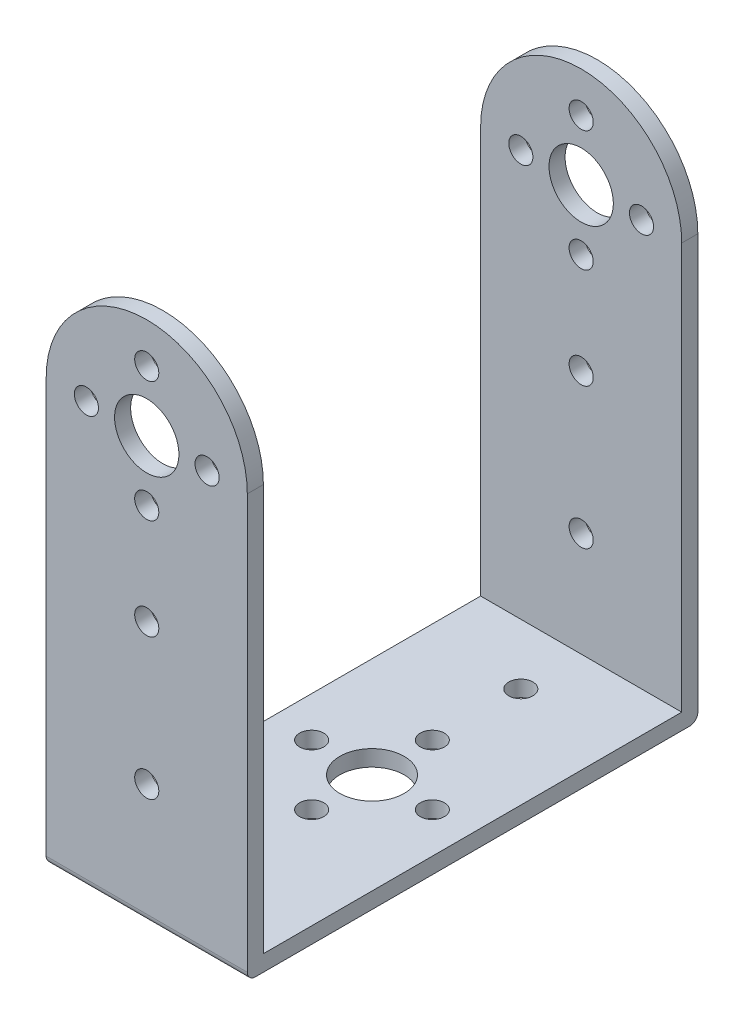
SolidWorks part; units mm, degrees
material "1060 Alloy"
ref_plane "Front Plane" through (0, 0, 0) normal (0, 0, 1) x (1, 0, 0)
ref_plane "Top Plane" through (0, 0, 0) normal (0, 1, 0) x (1, 0, 0)
ref_plane "Right Plane" through (0, 0, 0) normal (1, 0, 0) x (0, 0, -1)
sketch "Sketch1" plane through (0, 0, 0) normal (0, 0, 1) x (1, 0, 0)
  line L0 (-12.5, 32.5) -> (12.5, 7.5) construction
  line L1 (12.5, -32.5) -> (-12.5, -32.5)
  line L2 (12.5, -32.5) -> (12.5, 32.5)
  line L3 (12.5, 32.5) -> (-12.5, 32.5)
  line L4 (-12.5, -32.5) -> (-12.5, 32.5)
  line L5 (12.5, -32.5) -> (-12.5, 32.5) construction
  line L6 (12.5, 32.5) -> (-12.5, -32.5) construction
  line L7 (-12.5, 32.5) -> (12.5, 32.5)
  line L8 (-12.5, 32.5) -> (-12.5, 7.5)
  line L9 (-12.5, 7.5) -> (12.5, 7.5) construction
  line L10 (12.5, 32.5) -> (12.5, 7.5)
  line L11 (12.5, 7.5) -> (-12.5, 7.5) construction
  line L12 (-12.5, 7.5) -> (12.5, 32.5) construction
  line L13 (0, 32.5) -> (0, -32.5) construction
  circle A0 centre (0, 20) radius 4
  arc A1 (12.5, 20) -> (-12.5, 20) centre (0, 20) ccw
  circle A2 centre (0, 20) radius 7.5 construction
  circle A3 centre (-7.5, 20) radius 1.5
  circle A4 centre (0, 27.5) radius 1.5
  circle A5 centre (7.5, 20) radius 1.5
  circle A6 centre (0, 12.5) radius 1.5
  circle A7 centre (0, -17.5) radius 1.5
  circle A8 centre (0, 0) radius 1.5
  point P0 (0, 0)
  point P23 (0, 20)
  dimension "D4" = 8
  dimension "D5" = 15
  dimension "D6" = 3
  dimension "D8" = 3
  dimension "D9" = 15
  dimension "D10" = 17.5
  dimension "D11" = 3
  dimension "D1" = 65
  dimension "D2" = 25
  dimension "D3" = 25
  dimension "D7" = 4
extrude "Boss-Extrude1" add sketch "Sketch1" along normal blind 2 contours L2 A1 L4 L1 A6 A5 A4 A3 A0
ref_plane "Plane1" through (0, 0, 54) normal (0, 0, 1) x (1, 0, 0)
sketch "Sketch5" plane through (0, 0, 54) normal (0, 0, 1) x (1, 0, 0)
  line L0 (-12.5, 32.5) -> (12.5, 7.5) construction
  line L1 (12.5, -32.5) -> (-12.5, -32.5)
  line L2 (12.5, -32.5) -> (12.5, 32.5)
  line L3 (12.5, 32.5) -> (-12.5, 32.5)
  line L4 (-12.5, -32.5) -> (-12.5, 32.5)
  line L5 (12.5, -32.5) -> (-12.5, 32.5) construction
  line L6 (12.5, 32.5) -> (-12.5, -32.5) construction
  line L7 (-12.5, 32.5) -> (12.5, 32.5)
  line L8 (-12.5, 32.5) -> (-12.5, 7.5)
  line L9 (-12.5, 7.5) -> (12.5, 7.5) construction
  line L10 (12.5, 32.5) -> (12.5, 7.5)
  line L11 (12.5, 7.5) -> (-12.5, 7.5) construction
  line L12 (-12.5, 7.5) -> (12.5, 32.5) construction
  line L13 (0, 32.5) -> (0, -32.5) construction
  circle A0 centre (0, 20) radius 4
  arc A1 (12.5, 20) -> (-12.5, 20) centre (0, 20) ccw
  circle A2 centre (0, 20) radius 7.5 construction
  circle A3 centre (-7.5, 20) radius 1.5
  circle A4 centre (0, 27.5) radius 1.5
  circle A5 centre (7.5, 20) radius 1.5
  circle A6 centre (0, 12.5) radius 1.5
  circle A7 centre (0, -17.5) radius 1.5
  circle A8 centre (0, 0) radius 1.5
  point P0 (0, 0)
  point P22 (0, 20)
extrude "Boss-Extrude4" add sketch "Sketch5" along normal blind 2 separate body contours L2 A1 L4 L1 A8 A7 A6 A5 A4 A3 A0
sketch "Sketch6" plane through (0, -32.5, 0) normal (0, -1, 0) x (1, 0, 0)
  line L1 (-12.5, 0) -> (12.5, 0)
  line L2 (-12.5, 0) -> (-12.5, 56)
  line L3 (-12.5, 56) -> (12.5, 56)
  line L4 (12.5, 0) -> (12.5, 56)
extrude "Boss-Extrude5" add sketch "Sketch6" against normal blind 2
fillet "Fillet2" radius 1 2 edges at (0, -32.5, 56) (0, -32.5, 0)
sketch "Sketch7" plane through (0, -32.5, 0) normal (0, -1, 0) x (-1, 0, 0)
  line L0 (12.5, -56) -> (-12.5, 0) construction
  line L1 (-12.5, -56) -> (12.5, 0) construction
  line L2 (0, -55) -> (0, 0) construction
  line L3 (-12.5, -55) -> (12.5, -55) construction
  circle A0 centre (0, -28) radius 4
  circle A1 centre (0, -28) radius 7.5 construction
  circle A2 centre (7.5, -28) radius 1.5
  circle A3 centre (0, -35.5) radius 1.5
  circle A4 centre (-7.5, -28) radius 1.5
  circle A5 centre (0, -20.5) radius 1.5
  circle A6 centre (0, -46.5) radius 1.5
  circle A7 centre (0, -9.5) radius 1.5
  point P22 (0, -28)
  dimension "D1" = 8
  dimension "D2" = 15
  dimension "D3" = 3
  dimension "D5" = 3
  dimension "D6" = 18.5
  dimension "D7" = 3
  dimension "D8" = 18.5
  dimension "D4" = 4
extrude "Cut-Extrude1" cut sketch "Sketch7" against normal blind 2
